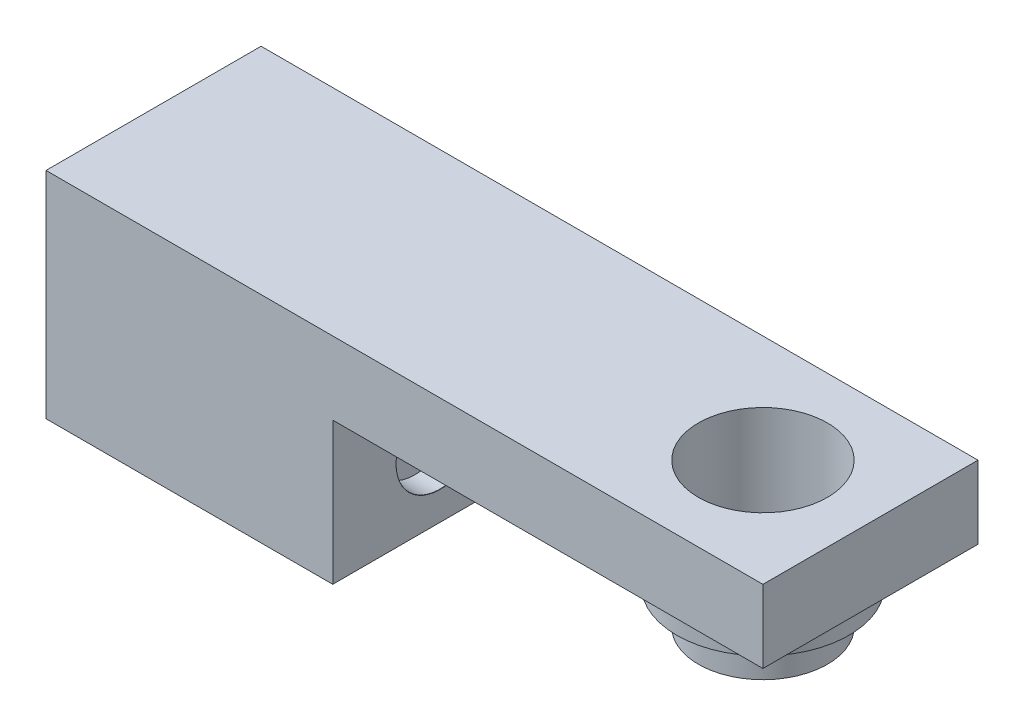
SolidWorks part; units mm, degrees
ref_plane "Спереди" through (0, 0, 0) normal (0, 0, 1) x (1, 0, 0)
ref_plane "Сверху" through (0, 0, 0) normal (0, 1, 0) x (1, 0, 0)
ref_plane "Справа" through (0, 0, 0) normal (1, 0, 0) x (0, 0, -1)
sketch "Эскиз1" plane through (0, 0, 0) normal (1, 0, 0) x (0, 0, -1)
  line L1 (-39.6578, -7.639) -> (-9.6578, -7.639)
  line L2 (-39.6578, -7.639) -> (-39.6578, 22.361)
  line L3 (-39.6578, 22.361) -> (-9.6578, 22.361)
  line L4 (-9.6578, -7.639) -> (-9.6578, 22.361)
extrude "Бобышка-Вытянуть1" add sketch "Эскиз1" along normal blind 40
sketch "Эскиз2" plane through (40, 0, 0) normal (1, 0, 0) x (0, 0, -1)
  line L0 (-24.6578, 22.361) -> (-24.6578, -9.226) construction
  line L1 (-9.6578, 22.361) -> (-39.6578, 22.361) construction
  line L2 (-9.6578, 7.361) -> (-46.9913, 7.361) construction
  line L3 (-9.6578, -7.639) -> (-9.6578, 22.361) construction
  line L4 (-46.9913, 12.1952) -> (-2.5903, 12.1952) construction
  line L6 (-39.6578, 22.361) -> (-9.6578, 22.361)
  line L7 (-39.6578, 22.361) -> (-39.6578, 12.1952)
  line L8 (-39.6578, 12.1952) -> (-9.6578, 12.1952)
  line L9 (-9.6578, 22.361) -> (-9.6578, 12.1952)
extrude "Бобышка-Вытянуть2" add sketch "Эскиз2" along normal blind 60
sketch "Эскиз3" plane through (0, 12.1952, 0) normal (0, -1, 0) x (1, 0, 0)
  line L0 (100, 24.6578) -> (85, 24.6578) construction
  line L1 (100, 39.6578) -> (100, 9.6578) construction
  line L2 (85, 24.6578) -> (85, 9.6578) construction
  line L3 (100, 9.6578) -> (40, 9.6578) construction
  circle A0 centre (85, 24.6578) radius 12
  point P6 (84.467, 24.6578)
  dimension "D1" = 15
  dimension "D2" = 15
extrude "Бобышка-Вытянуть3" add sketch "Эскиз3" along normal blind 5
sketch "Эскиз4" plane through (0, 7.1952, 0) normal (0, -1, 0) x (1, 0, 0)
  line L0 (97, 24.6578) -> (69.3301, 24.6578) construction
  line L1 (85, 24.6578) -> (85, 37.9572) construction
  circle A0 centre (85, 24.6578) radius 12 construction
  circle A1 centre (85, 24.6578) radius 12 construction
  circle A2 centre (85, 24.6578) radius 9
extrude "Бобышка-Вытянуть4" add sketch "Эскиз4" along normal blind 5
hole_wizard "Цековка для  болта с шестигранной головкой M51" positions "Эскиз12" profile "Эскиз13" counterbore size "M5" standard "ISO" end condition through all
sketch "Эскиз12" plane through (40, 0, 0) normal (1, 0, 0) x (0, 0, -1)
  point P0 (-24.682, 2.4825)
sketch "Эскиз13" plane through (40, 2.4825, 24.682) normal (0, 1, 0) x (0, 0, -1)
  line L0 (0, 0) -> (0, 40)
  line L1 (0, 40) -> (2.75, 40)
  line L3 (2.75, 40) -> (2.75, 3.5)
  line L4 (6.119, 3.5) -> (2.75, 3.5)
  line L5 (6.119, 3.5) -> (6.119, 0.025)
  line L6 (6.119, 0.025) -> (6.144, 0)
  line L7 (6.144, 0) -> (0, 0)
  line L8 (-6.119, 0.025) -> (-6.144, 0) construction
  line L11 (0, -6.35) -> (0, 107.95) construction
  dimension "Диаметр сквозного отверстия" = 5.5
  dimension "Глубина сквозного отверстия" = 40
  dimension "Диаметр цековки" = 12.238
  dimension "Глубина цековки" = 3.5
  dimension "Диаметр передней зенковки" = 12.288
  dimension "Угол передней зенковки" = 90
sketch "Эскиз16" plane through (0, 22.361, 0) normal (0, 1, 0) x (1, 0, 0)
  line L0 (100, -24.6578) -> (85, -24.6578) construction
  line L1 (100, -9.6578) -> (100, -39.6578) construction
  line L2 (85, -24.6578) -> (85, -39.6578) construction
  line L3 (100, -39.6578) -> (0, -39.6578) construction
  circle A0 centre (85, -24.6578) radius 9
  dimension "D1" = 15
  dimension "D2" = 15
extrude "Вырез-Вытянуть1" cut sketch "Эскиз16" against normal blind 15
